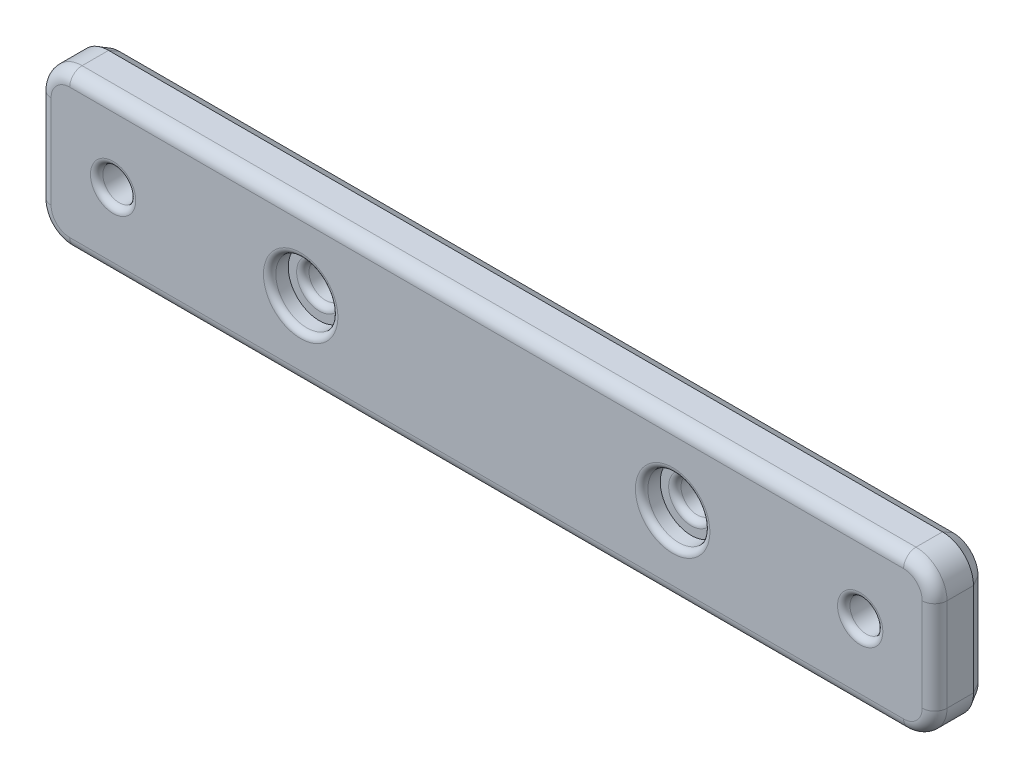
SolidWorks part; units mm, degrees
ref_plane "Front Plane" through (0, 0, 0) normal (0, 0, 1) x (1, 0, 0)
ref_plane "Top Plane" through (0, 0, 0) normal (0, 1, 0) x (1, 0, 0)
ref_plane "Right Plane" through (0, 0, 0) normal (1, 0, 0) x (0, 0, -1)
sketch "Sketch2" plane through (0, 0, 0) normal (0, 0, 1) x (1, 0, 0)
  line L1 (-72.25, -12.5) -> (72.25, -12.5)
  line L2 (-72.25, -12.5) -> (-72.25, 12.5)
  line L3 (-72.25, 12.5) -> (72.25, 12.5)
  line L4 (72.25, -12.5) -> (72.25, 12.5)
  line L5 (-72.25, -12.5) -> (72.25, 12.5) construction
  line L6 (-72.25, 12.5) -> (72.25, -12.5) construction
  point P0 (0, 0)
  dimension "D1" = 144.5
  dimension "D2" = 25
extrude "Boss-Extrude1" add sketch "Sketch2" along normal blind 8
sketch "Sketch3" plane through (0, 0, 8) normal (0, 0, 1) x (1, 0, 0)
  line L0 (-72.25, 12.5) -> (-72.25, -12.5) construction
  line L1 (-60.25, 0) -> (-30, 0) construction
  line L2 (30, 0) -> (60.25, 0) construction
  line L6 (30, 0) -> (-30, 0) construction
  circle A0 centre (-60.25, 0) radius 2.65
  circle A1 centre (60.25, 0) radius 2.65
  circle A5 centre (-30, 0) radius 2.65
  circle A6 centre (30, 0) radius 2.65
  dimension "D1" = 5.3
  dimension "D3" = 12
  dimension "D4" = 120.5
  dimension "D6" = 60
extrude "Cut-Extrude1" cut sketch "Sketch3" against normal through all
sketch "Sketch4" plane through (0, 0, 8) normal (0, 0, 1) x (1, 0, 0)
  circle A0 centre (-30, 0) radius 5
  circle A1 centre (30, 0) radius 5
  dimension "D1" = 10
extrude "Cut-Extrude2" cut sketch "Sketch4" against normal blind 3
fillet "Fillet1" radius 5 4 edges at (-72.25, -12.5, 4) (-72.25, 12.5, 4) (72.25, -12.5, 4) (72.25, 12.5, 4)
fillet "Fillet2" radius 2 8 edges at (70.7855, 11.0355, 8) (72.25, 0, 8) (70.7855, -11.0355, 8) (0, -12.5, 8) (-70.7855, -11.0355, 8) (-72.25, 0, 8) (-70.7855, 11.0355, 8) (0, 12.5, 8)
fillet "Fillet3" radius 1 6 edges at (62.9, 0, 8) (-57.6, 0, 8) (32.65, 0, 5) (-27.35, 0, 5) (35, 0, 8) (-25, 0, 8)
chamfer "Chamfer1" distance 1 angle 60 8 edges at (0, 12.5, 0) (-70.7855, 11.0355, 0) (70.7855, 11.0355, 0) (-72.25, 0, 0) (72.25, 0, 0) (-70.7855, -11.0355, 0) (70.7855, -11.0355, 0) (0, -12.5, 0)
chamfer "Chamfer2" distance 1 angle 30 4 edges at (62.9, 0, 0) (32.65, 0, 0) (-27.35, 0, 0) (-57.6, 0, 0)
